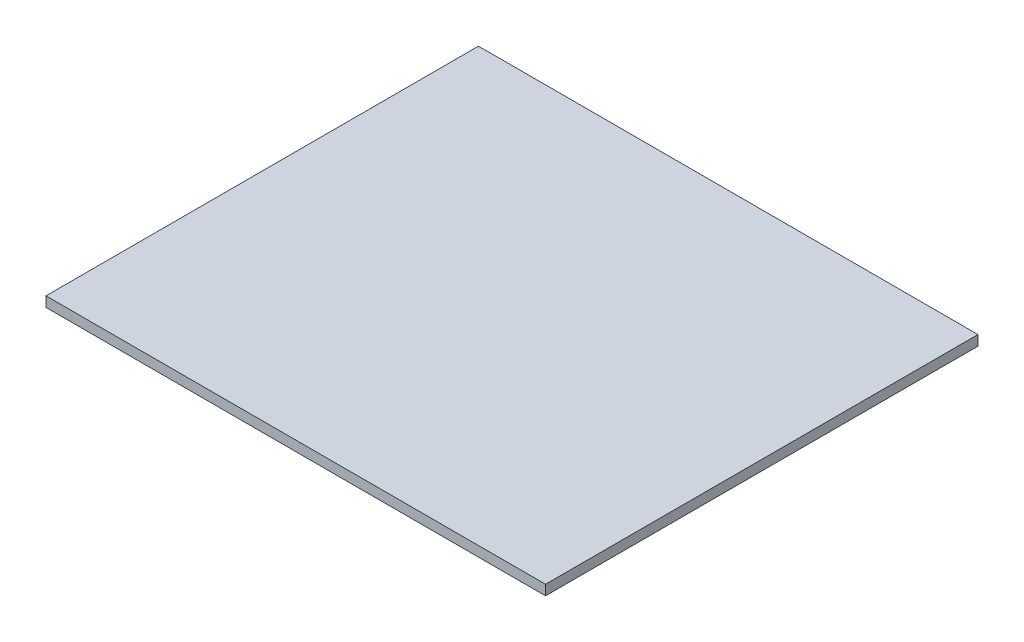
SolidWorks part; units mm, degrees
ref_plane "Front Plane" through (0, 0, 0) normal (0, 0, 1) x (1, 0, 0)
ref_plane "Top Plane" through (0, 0, 0) normal (0, 1, 0) x (1, 0, 0)
ref_plane "Right Plane" through (0, 0, 0) normal (1, 0, 0) x (0, 0, -1)
sketch "Sketch1" plane through (0, 0, 0) normal (0, 1, 0) x (1, 0, 0)
  line L1 (-74.5, 64.5) -> (74.5, 64.5)
  line L2 (-74.5, 64.5) -> (-74.5, -64.5)
  line L3 (-74.5, -64.5) -> (74.5, -64.5)
  line L4 (74.5, 64.5) -> (74.5, -64.5)
  line L5 (-74.5, 64.5) -> (74.5, -64.5) construction
  line L6 (-74.5, -64.5) -> (74.5, 64.5) construction
  point P0 (0, 0)
  dimension "D1" = 149
  dimension "D2" = 129
extrude "Boss-Extrude1" add sketch "Sketch1" along normal blind 3
